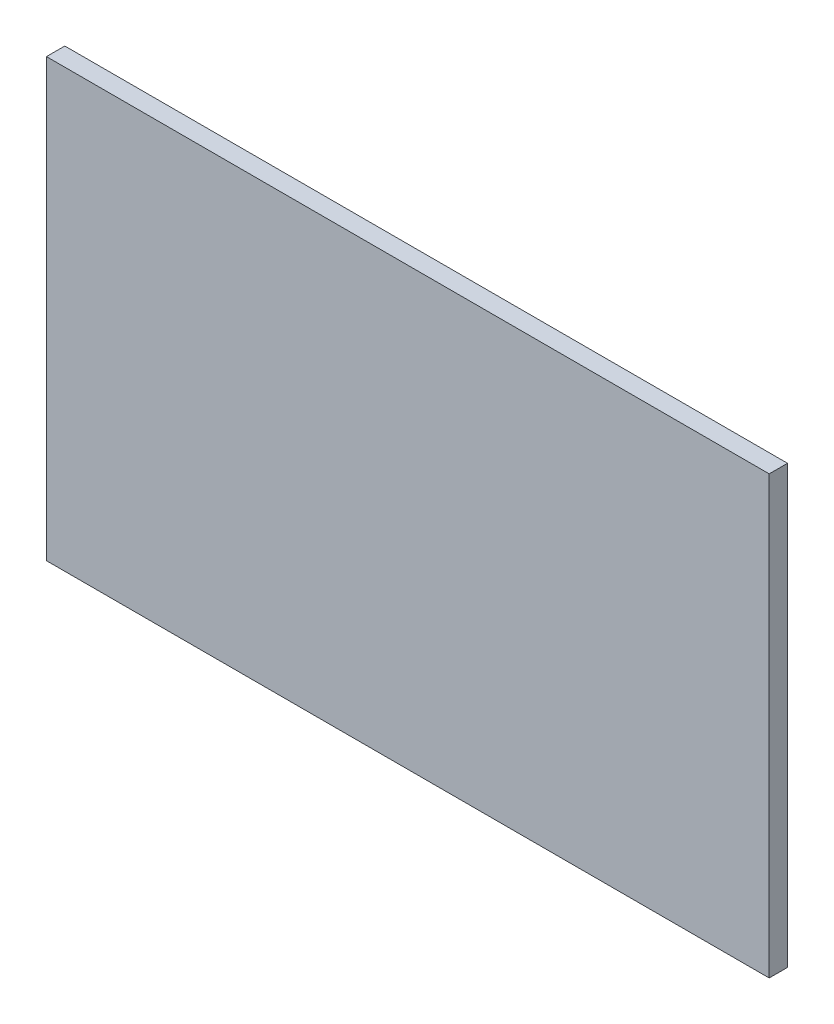
SolidWorks part; units mm, degrees
ref_plane "Plano frontal" through (0, 0, 0) normal (0, 0, 1) x (1, 0, 0)
ref_plane "Plano superior" through (0, 0, 0) normal (0, 1, 0) x (1, 0, 0)
ref_plane "Plano direito" through (0, 0, 0) normal (1, 0, 0) x (0, 0, -1)
sketch "Sketch1" plane through (0, 0, 0) normal (0, 0, 1) x (1, 0, 0)
  line L1 (1270.6593, -4483) -> (1090.6593, -4483)
  line L2 (1270.6593, -4483) -> (1270.6593, -3883)
  line L3 (1270.6593, -3883) -> (1090.6593, -3883)
  line L4 (1090.6593, -4483) -> (1090.6593, -3883)
  line L5 (-169.3407, -4483) -> (-349.3407, -4483)
  line L6 (-169.3407, -4483) -> (-169.3407, -3883)
  line L7 (-169.3407, -3883) -> (-349.3407, -3883)
  line L8 (-349.3407, -4483) -> (-349.3407, -3883)
extrude "Boss-Extrude1" add sketch "Sketch1" along normal blind 1000
sketch "Sketch2" plane through (0, 0, 1000) normal (0, 0, 1) x (1, 0, 0)
  line L2 (3487.1301, -6563.4798) -> (3487.1301, -1802.5202)
  line L3 (3487.1301, -6563.4798) -> (-4393.9611, -6563.4798)
  line L5 (3487.1301, -1802.5202) -> (-4393.9611, -1802.5202)
  line L6 (-4393.9611, -6563.4798) -> (-4393.9611, -1802.5202)
extrude "Boss-Extrude2" add sketch "Sketch2" along normal blind 200
